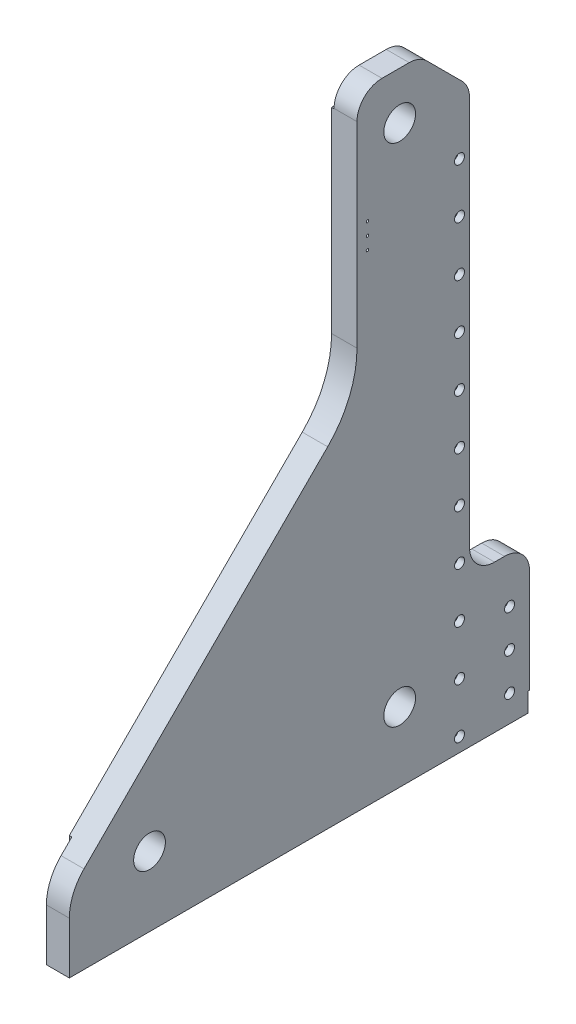
SolidWorks part; units mm, degrees
material "Low Carbon Steel"
ref_plane "Front Plane" through (0, 0, 0) normal (0, 0, 1) x (1, 0, 0)
ref_plane "Top Plane" through (0, 0, 0) normal (0, 1, 0) x (1, 0, 0)
ref_plane "Right Plane" through (0, 0, 0) normal (1, 0, 0) x (0, 0, -1)
sketch "Sketch1" plane through (0, 0, 0) normal (1, 0, 0) x (0, 0, -1)
  line L0 (0, 350) -> (0, 1129.2893)
  line L1 (-120.7107, 1250) -> (-175, 1250)
  line L2 (-225, 1200) -> (-225, 807.8427)
  line L3 (-283.5786, 666.4214) -> (-770.7107, 179.2893)
  line L4 (-800, 108.5786) -> (-800, 0)
  line L5 (-85.3553, 1235.3553) -> (-14.6447, 1164.6447)
  line L6 (0, 0) -> (120, 0)
  line L7 (-800, 0) -> (0, 0)
  line L9 (50, 300) -> (70, 300)
  line L10 (120, 0) -> (120, 250)
  arc A0 (-770.7107, 179.2893) -> (-800, 108.5786) centre (-700, 108.5786) ccw
  arc A1 (-225, 807.8427) -> (-283.5786, 666.4214) centre (-425, 807.8427) cw
  arc A2 (0, 350) -> (50, 300) centre (50, 350) ccw
  arc A3 (70, 300) -> (120, 250) centre (70, 250) cw
  arc A4 (-14.6447, 1164.6447) -> (0, 1129.2893) centre (-50, 1129.2893) cw
  arc A5 (-85.3553, 1235.3553) -> (-120.7107, 1250) centre (-120.7107, 1200) ccw
  arc A6 (-175, 1250) -> (-225, 1200) centre (-175, 1200) ccw
  point P8 (-800, 150)
  point P12 (-225, 725)
  point P18 (0, 300)
  point P21 (120, 300)
  point P27 (-100, 1250)
  point P30 (-225, 1250)
  dimension "D6" = 100
  dimension "D7" = 200
  dimension "D10" = 50
  dimension "D13" = 50
  dimension "D1" = 45
  dimension "D2" = 225
  dimension "D3" = 150
  dimension "D4" = 575
  dimension "D5" = 125
  dimension "D8" = 120
  dimension "D9" = 300
  dimension "D11" = 920
  dimension "D12" = 1250
extrude "Boss-Extrude1" add sketch "Sketch1" along normal blind 50.8
sketch "Sketch2" plane through (0, 1250, 0) normal (0, 1, 0) x (1, 0, 0)
  line L0 (0, -120.7107) -> (0, -175) construction
  line L1 (0, 5) -> (20, 5)
  line L2 (0, 5) -> (0, -50)
  line L3 (0, -50) -> (20, -50)
  line L4 (20, 5) -> (20, -50)
  line L6 (50.8, 0) -> (0, 0) construction
  dimension "D1" = 50
  dimension "D2" = 20
  dimension "D3" = 5
extrude "Cut-Extrude1" cut sketch "Sketch2" against normal through all
sketch "Sketch3" plane through (0, 0, 800) normal (0, 0, -1) x (-1, 0, 0)
  line L0 (-50.8, 0) -> (-50.8, 1250) construction
  line L1 (0, 0) -> (-50.8, 0)
  line L2 (0, 0) -> (0, 5)
  line L3 (0, 5) -> (-50.8, 5)
  line L4 (-50.8, 0) -> (-50.8, 5)
  dimension "D1" = 5
extrude "Cut-Extrude2" cut sketch "Sketch3" along normal through all
sketch "Sketch5" plane through (0, 0, 0) normal (1, 0, 0) x (0, 0, -1)
  line L1 (5, 328.2055) -> (120, 328.2055)
  line L2 (5, 328.2055) -> (5, 5)
  line L3 (5, 5) -> (120, 5)
  line L4 (120, 328.2055) -> (120, 5)
extrude "Cut-Extrude5" cut sketch "Sketch5" along direction (1, 0, 0) on the side of the normal offset from surface (5 mm away) 15
hole_wizard "M6 Tapped Hole1" positions "Sketch7" profile "Sketch6" tap size "M6" standard "Peddi DIN"
sketch "Sketch7" plane through (50.8, 0, 0) normal (1, 0, 0) x (0, 0, -1)
  line L0 (-204, 1017) -> (-204, 967) construction
  line L2 (120, 5) -> (-800, 5) construction
  line L3 (-50, 5) -> (-50, 1200) construction
  point P0 (-204, 1017)
  point P2 (-204, 967)
  point P12 (-204, 992)
  dimension "D1" = 50
  dimension "D2" = 962
  dimension "D3" = 154
sketch "Sketch6" plane through (50.8, 1017, 204) normal (0, 1, 0) x (0, 0, -1)
  line L0 (0, 0) -> (0, 21.5022)
  line L1 (0, 21.5022) -> (2.5, 20)
  line L2 (2.5, 20) -> (2.5, 0)
  line L5 (2.5, 0) -> (0, 0)
  line L10 (0, 21.5022) -> (-2.5, 20) construction
  line L11 (0, -6.35) -> (0, 107.95) construction
  dimension "Tap Drill Dia." = 5
  dimension "Tap Drill Depth" = 20
  dimension "Drill Angle" = 118
cosmetic thread "Hole Thread1" parameters "D1"=15, "D2"=6
cosmetic thread "Hole Thread2" parameters "D1"=15, "D2"=6
cosmetic thread "Hole Thread3" parameters "D1"=15, "D2"=6
hole_wizard "CBORE for M12 Hex Socket Head Cap Screw1" positions "Sketch8" profile "Sketch9" counterbore size "M12" standard "Peddi DIN" end condition through all
sketch "Sketch8" plane through (50.8, 0, 0) normal (1, 0, 0) x (0, 0, -1)
  line L2 (-50, 5) -> (-50, 1200) construction
  line L3 (120, 5) -> (-800, 5) construction
  line L4 (-20, 33) -> (-20, 133) construction
  line L5 (-20, 133) -> (-20, 233) construction
  line L6 (-20, 233) -> (-20, 333) construction
  line L7 (-20, 333) -> (-20, 433) construction
  line L8 (-20, 433) -> (-20, 533) construction
  line L9 (-20, 533) -> (-20, 633) construction
  line L10 (-20, 633) -> (-20, 733) construction
  line L11 (-20, 733) -> (-20, 833) construction
  line L12 (-20, 833) -> (-20, 933) construction
  line L13 (-20, 933) -> (-20, 1033) construction
  line L16 (80, 58) -> (80, 133) construction
  line L17 (80, 133) -> (80, 208) construction
  line L18 (-20, 133) -> (80, 133) construction
  point P0 (-20, 33)
  point P13 (-20, 133)
  point P15 (-20, 233)
  point P17 (-20, 333)
  point P18 (-20, 433)
  point P20 (-20, 533)
  point P22 (-20, 633)
  point P24 (-20, 733)
  point P26 (-20, 833)
  point P28 (-20, 933)
  point P30 (-20, 1033)
  point P35 (80, 58)
  point P37 (80, 133)
  point P39 (80, 208)
  dimension "D1" = 28
  dimension "D2" = 30
  dimension "D3" = 100
  dimension "D4" = 100
  dimension "D5" = 75
sketch "Sketch9" plane through (50.8, 33, 20) normal (0, 1, 0) x (0, 0, -1)
  line L0 (0, 0) -> (0, 50.8)
  line L1 (0, 50.8) -> (6.75, 50.8)
  line L3 (6.75, 50.8) -> (6.75, 13)
  line L4 (6.75, 13) -> (10, 13)
  line L5 (10, 13) -> (10, 0)
  line L7 (10, 0) -> (0, 0)
  line L11 (0, -6.35) -> (0, 107.95) construction
  dimension "Thru Hole Dia." = 13.5
  dimension "Thru Hole Depth" = 50.8
  dimension "C'Bore Dia." = 20
  dimension "C'Bore Depth" = 13
hole_wizard "M12 Tapped Hole1" positions "Sketch12" profile "Sketch13" tap size "M12" standard "Peddi DIN"
sketch "Sketch12" plane through (0, 5, 0) normal (0, -1, 0) x (-1, 0, 0)
  line L0 (-25, 120) -> (-25, 90) construction
  line L1 (-5, 120) -> (-50.8, 120) construction
  line L2 (-25, 90) -> (-25, 30) construction
  line L3 (-25, 30) -> (-25, -60) construction
  line L4 (-25, -60) -> (-25, -140) construction
  line L5 (-25, -140) -> (-25, -220) construction
  line L6 (-25, -220) -> (-25, -300) construction
  line L7 (-25, -300) -> (-25, -380) construction
  line L8 (-25, -380) -> (-25, -460) construction
  line L9 (-25, -460) -> (-25, -540) construction
  line L10 (-25, -540) -> (-25, -620) construction
  line L11 (-25, -620) -> (-25, -710) construction
  line L12 (-25, -710) -> (-25, -770) construction
  line L14 (-5, 5) -> (-5, 120) construction
  line L15 (-25, -770) -> (-25, -800) construction
  line L17 (0, -800) -> (-50.8, -800) construction
  line L18 (0, -50) -> (-20, -50) construction
  point P1 (-25, 90)
  point P5 (-25, 30)
  point P7 (-25, -60)
  point P9 (-25, -140)
  point P10 (-25, -220)
  point P12 (-25, -300)
  point P14 (-25, -380)
  point P16 (-25, -460)
  point P18 (-25, -540)
  point P20 (-25, -620)
  point P22 (-25, -710)
  point P24 (-25, -770)
  dimension "D1" = 140
  dimension "D2" = 60
  dimension "D3" = 90
  dimension "D4" = 80
  dimension "D5" = 20
sketch "Sketch13" plane through (25, 5, 770) normal (1, 0, 0) x (0, 0, -1)
  line L0 (0, 0) -> (0, 47.0544)
  line L1 (0, 47.0544) -> (5.1, 43.99)
  line L2 (5.1, 43.99) -> (5.1, 0)
  line L5 (5.1, 0) -> (0, 0)
  line L10 (0, 47.0544) -> (-5.1, 43.99) construction
  line L11 (0, -6.35) -> (0, 107.95) construction
  dimension "Tap Drill Dia." = 10.2
  dimension "Tap Drill Depth" = 43.99
  dimension "Drill Angle" = 118
cosmetic thread "Hole Thread4" parameters "D1"=30, "D2"=12
cosmetic thread "Hole Thread5" parameters "D1"=30, "D2"=12
cosmetic thread "Hole Thread6" parameters "D1"=30, "D2"=12
cosmetic thread "Hole Thread7" parameters "D1"=30, "D2"=12
cosmetic thread "Hole Thread8" parameters "D1"=30, "D2"=12
cosmetic thread "Hole Thread9" parameters "D1"=30, "D2"=12
cosmetic thread "Hole Thread10" parameters "D1"=30, "D2"=12
cosmetic thread "Hole Thread11" parameters "D1"=30, "D2"=12
cosmetic thread "Hole Thread12" parameters "D1"=30, "D2"=12
cosmetic thread "Hole Thread13" parameters "D1"=30, "D2"=12
cosmetic thread "Hole Thread14" parameters "D1"=30, "D2"=12
cosmetic thread "Hole Thread15" parameters "D1"=30, "D2"=12
fillet "Fillet1" radius 0.7937 2 edges at (20, 166.6028, -5) (20, 602.5, 50)
sketch "Sketch14" plane through (5, 0, 0) normal (-1, 0, 0) x (0, 0, 1)
  line L0 (0, 350) -> (0, 1129.2893) construction
  line L1 (225, 1250) -> (0, 1250)
  line L2 (225, 1250) -> (225, 1199.2)
  line L3 (225, 1199.2) -> (0, 1199.2)
  line L4 (0, 1250) -> (0, 1199.2)
  line L5 (283.5786, 666.4214) -> (770.7107, 179.2893) construction
  line L6 (800, 5) -> (749.2, 5)
  line L7 (800, 5) -> (800, 200.8)
  line L8 (800, 200.8) -> (749.2, 200.8)
  line L9 (749.2, 5) -> (749.2, 200.8)
  line L10 (120.7107, 1250) -> (175, 1250) construction
  line L11 (225, 1200) -> (225, 807.8427) construction
  dimension "D1" = 50.8
  dimension "D2" = 50.8
extrude "Cut-Extrude6" cut sketch "Sketch14" along normal through all
sketch "Sketch15" plane through (0, 0, 0) normal (-1, 0, 0) x (0, 0, 1)
  line L0 (50, 5) -> (749.2, 5) construction
  line L1 (-120, 5) -> (-116.825, 5)
  line L2 (-120, 5) -> (-120, 43.1)
  line L3 (-120, 43.1) -> (-116.825, 43.1)
  line L4 (-116.825, 5) -> (-116.825, 43.1)
  line L5 (-120, 5) -> (-120, 250) construction
  circle A0 centre (139.6896, 144.2936) radius 31.75
  dimension "D4" = 63.5
  dimension "D1" = 38.1
  dimension "D2" = 3.175
  dimension "D3" = 139.2936
  dimension "D5" = 259.6896
extrude "Cut-Extrude7" cut sketch "Sketch15" against normal through all
sketch "Sketch16" plane through (50.8, 0, 0) normal (1, 0, 0) x (0, 0, -1)
  line L0 (-639.6896, 144.2936) -> (-139.6896, 144.2936) construction
  line L1 (-139.6896, 144.2936) -> (-139.6896, 1155) construction
  line L2 (116.825, 5) -> (-800, 5) construction
  circle A0 centre (-139.6896, 1155) radius 31.75
  circle A1 centre (-639.6896, 144.2936) radius 31.75
  circle A2 centre (-139.6896, 144.2936) radius 31.75 construction
  dimension "D1" = 1150
  dimension "D2" = 500
extrude "Cut-Extrude8" cut sketch "Sketch16" against normal through all
other "Freeze***"
